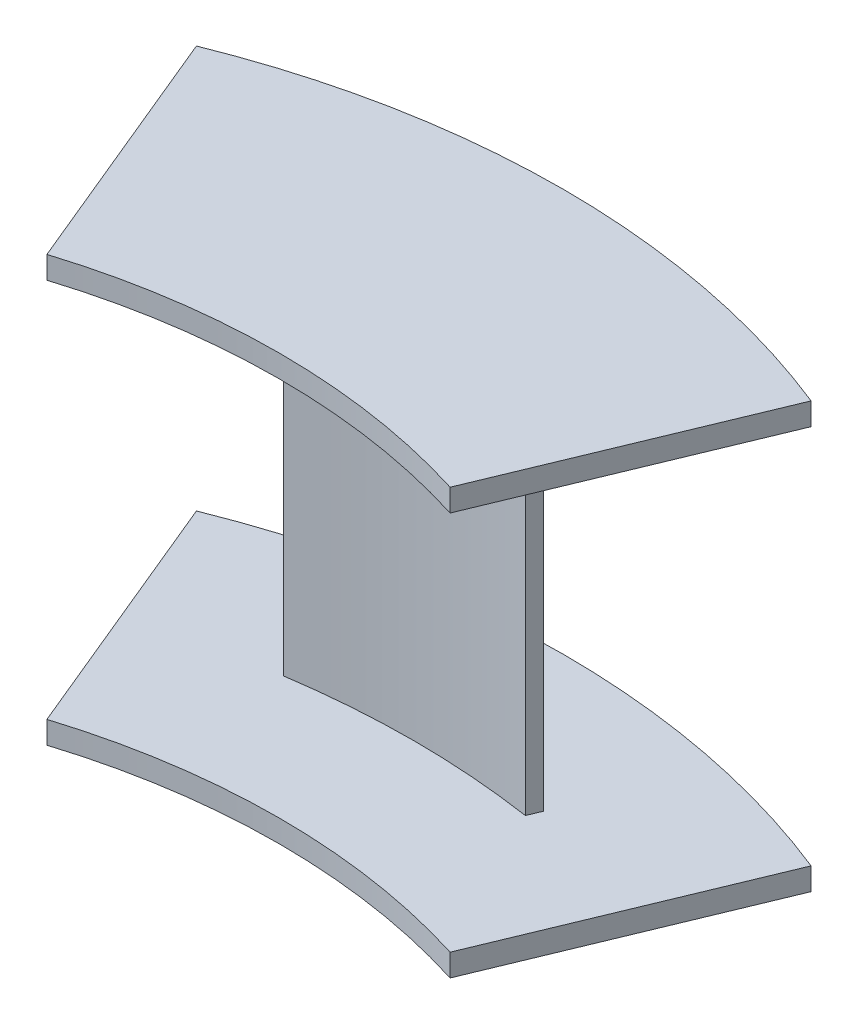
SolidWorks part; units mm, degrees
material "ABS"
ref_plane "Front Plane" through (0, 0, 0) normal (0, 0, 1) x (1, 0, 0)
ref_plane "Top Plane" through (0, 0, 0) normal (0, 1, 0) x (1, 0, 0)
ref_plane "Right Plane" through (0, 0, 0) normal (1, 0, 0) x (0, 0, -1)
sketch "Sketch1" plane through (0, 0, 0) normal (0, 1, 0) x (1, 0, 0)
  line L0 (-46.1695, -34.4931) -> (-69.8003, 22.5568)
  line L1 (43.9493, -34.4931) -> (67.5802, 22.5568)
  arc A0 (67.5802, 22.5568) -> (-69.8003, 22.5568) centre (-1.1101, -148.6133) ccw
  arc A1 (-46.1695, -34.4931) -> (43.9493, -34.4931) centre (-1.1101, -178.6133) cw
extrude "Boss-Extrude1" add sketch "Sketch1" along normal mid plane 5
sketch "Sketch2" plane through (0, 2.5, 0) normal (0, 1, 0) x (1, 0, 0)
  line L0 (-29.3217, 3.2266) -> (-28.1335, 0.358)
  line L1 (25.9133, 0.358) -> (27.1015, 3.2266)
  line L2 (43.9493, -34.4931) -> (67.5802, 22.5568)
  line L3 (-69.8003, 22.5568) -> (-46.1695, -34.4931)
  line L4 (43.9493, -34.4931) -> (67.5802, 22.5568) construction
  line L5 (-69.8003, 22.5568) -> (-46.1695, -34.4931) construction
  arc A0 (25.9133, 0.358) -> (-28.1335, 0.358) centre (-1.1101, -178.6133) ccw
  arc A1 (27.1015, 3.2266) -> (-29.3217, 3.2266) centre (-1.1101, -148.6133) ccw
  arc A2 (43.9493, -34.4931) -> (-46.1695, -34.4931) centre (-1.1101, -178.6133) ccw
  arc A3 (67.5802, 22.5568) -> (-69.8003, 22.5568) centre (-1.1101, -148.6133) ccw
  arc A4 (43.9493, -34.4931) -> (-46.1695, -34.4931) centre (-1.1101, -178.6133) ccw construction
  arc A5 (67.5802, 22.5568) -> (-69.8003, 22.5568) centre (-1.1101, -148.6133) ccw construction
  dimension "D1" = 0
  dimension "D2" = 30
extrude "Boss-Extrude2" add sketch "Sketch2" along normal blind 85
ref_plane "Plane1" through (0, 45, 0) normal (0, 1, 0) x (1, 0, 0)
mirror "Mirror1" about plane through (0, 45, 0) normal (0, 1, 0) of "Boss-Extrude1"
